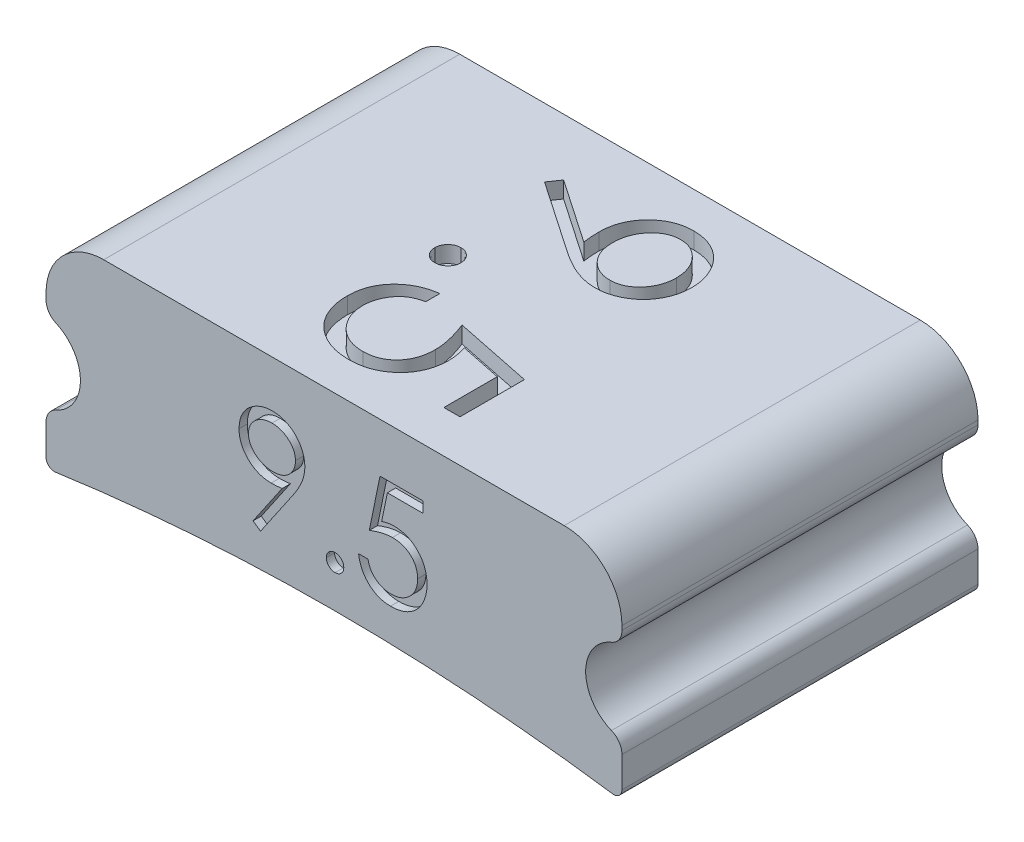
SolidWorks part; units mm, degrees
ref_plane "Front Plane" through (0, 0, 0) normal (0, 0, 1) x (1, 0, 0)
ref_plane "Top Plane" through (0, 0, 0) normal (0, 1, 0) x (1, 0, 0)
ref_plane "Right Plane" through (0, 0, 0) normal (1, 0, 0) x (0, 0, -1)
sketch "Sketch2" plane through (0, 0, 0) normal (0, 0, 1) x (1, 0, 0)
  line L0 (-27.925, 0) -> (27.925, 0)
  line L7 (-34.925, -7) -> (-34.925, -7.6947)
  line L8 (-34.925, -24.2459) -> (-34.925, -20.5432)
  line L9 (34.925, -7) -> (34.925, -7.5009)
  line L10 (34.925, -24.2459) -> (34.925, -20.5432)
  arc A0 (-33.785, -25.236) -> (33.785, -25.236) centre (0, -264.1592) cw
  arc A1 (-33.7194, -9.5511) -> (-33.7194, -18.6869) centre (-35.7527, -14.119) cw
  arc A2 (33.6533, -9.3853) -> (33.6533, -18.6589) centre (35.5242, -14.0221) ccw
  arc A3 (27.925, 0) -> (34.925, -7) centre (27.925, -7) cw
  arc A4 (-27.925, 0) -> (-34.925, -7) centre (-27.925, -7) ccw
  arc A5 (34.925, -20.5432) -> (33.6533, -18.6589) centre (32.893, -20.5432) ccw
  arc A6 (34.925, -7.5009) -> (33.6533, -9.3853) centre (32.893, -7.5009) cw
  arc A7 (-33.7194, -18.6869) -> (-34.925, -20.5432) centre (-32.893, -20.5432) ccw
  arc A8 (-34.925, -7.6947) -> (-33.7194, -9.5511) centre (-32.893, -7.6947) ccw
  arc A9 (34.925, -24.2459) -> (33.785, -25.236) centre (33.925, -24.2459) cw
  arc A10 (-34.925, -24.2459) -> (-33.785, -25.236) centre (-33.925, -24.2459) ccw
  point P0 (0, 0)
  point P4 (0, 0)
  point P23 (34.925, -9.0581)
  point P26 (-34.925, -19.05)
  point P29 (-34.925, -9.188)
  point P32 (34.925, -25.4)
  point P35 (-34.925, -25.4)
extrude "Boss-Extrude2" add sketch "Sketch2" along normal blind 43.18
sketch "Sketch3" plane through (0, 0, 43.18) normal (0, 0, 1) x (1, 0, 0)
  line L0 (-33.7194, -18.6869) -> (33.6533, -18.6589) construction
  text T0 "9.5\r\n" font "Century Gothic" height in points 48
extrude "Cut-Extrude1" cut sketch "Sketch3" against normal blind 1
sketch "Sketch4" plane through (0, 0, 0) normal (0, 0, -1) x (-1, 0, 0)
  line L0 (-33.6533, -18.6589) -> (33.7194, -18.6869) construction
  text T0 "9.5" font "Century Gothic" height in points 48
extrude "Cut-Extrude2" cut sketch "Sketch4" against normal blind 1
sketch "Sketch5" plane through (0, 0, 0) normal (0, 1, 0) x (1, 0, 0)
  line L0 (-8.875, 0) -> (-8.875, -43.18) construction
  line L1 (27.925, 0) -> (-27.925, 0) construction
  line L2 (27.925, -43.18) -> (-27.925, -43.18) construction
  line L3 (-27.925, -43.18) -> (-27.925, 0) construction
  text T0 "9.5" font "Century Gothic" height in points 72
  dimension "D1" = 19.05
extrude "Cut-Extrude3" cut sketch "Sketch5" against normal blind 2
equation "\"Radius\"=9.5"
equation "\"D1@Sketch2\"=\"Radius\""
